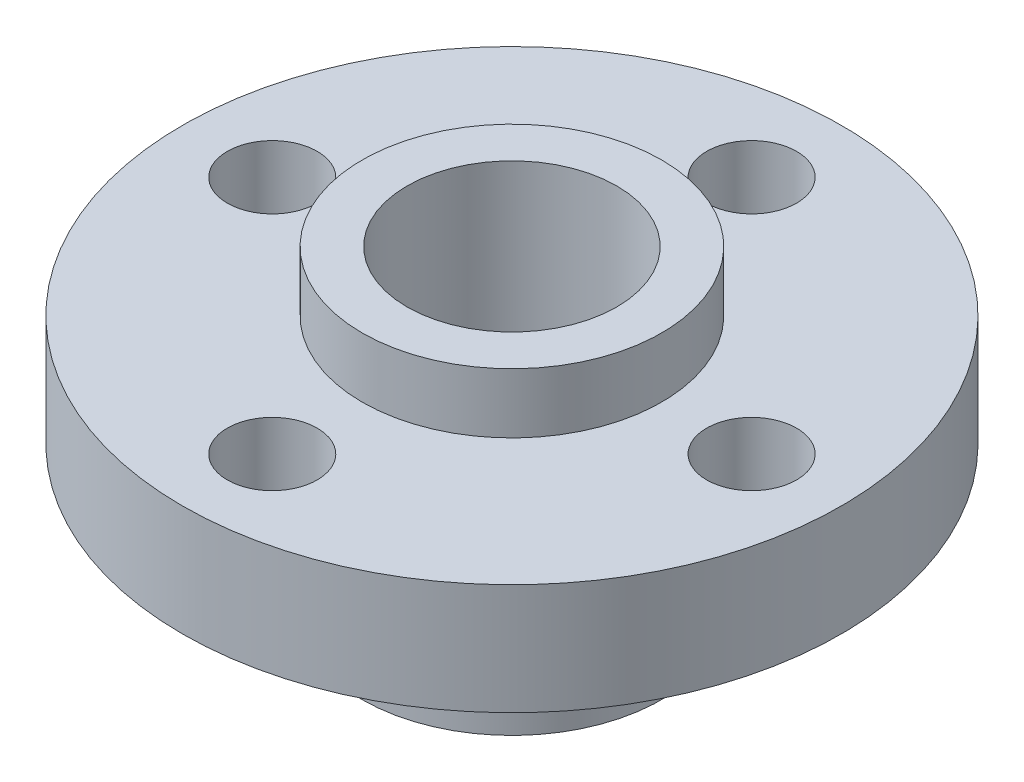
SolidWorks part; units mm, degrees
ref_plane "Front Plane" through (0, 0, 0) normal (0, 0, 1) x (1, 0, 0)
ref_plane "Top Plane" through (0, 0, 0) normal (0, 1, 0) x (1, 0, 0)
ref_plane "Right Plane" through (0, 0, 0) normal (1, 0, 0) x (0, 0, -1)
sketch "Sketch1" plane through (0, 0, 0) normal (0, 1, 0) x (1, 0, 0)
  circle A0 centre (0, 0) radius 11
  dimension "D1" = 22
extrude "Boss-Extrude1" add sketch "Sketch1" along normal blind 3.7
sketch "Sketch2" plane through (0, 3.7, 0) normal (0, 1, 0) x (1, 0, 0)
  circle A0 centre (0, 0) radius 8 construction
  circle A1 centre (0, 8) radius 1.5
  circle A2 centre (8, 0) radius 1.5
  circle A3 centre (0, -8) radius 1.5
  circle A4 centre (-8, 0) radius 1.5
  dimension "D1" = 16
  dimension "D2" = 3
extrude "Cut-Extrude1" cut sketch "Sketch2" against normal up to next
sketch "Sketch3" plane through (0, 3.7, 0) normal (0, 1, 0) x (1, 0, 0)
  circle A0 centre (0, 0) radius 5
  dimension "D1" = 10
extrude "Boss-Extrude2" add sketch "Sketch3" against normal blind 10.6 from offset 2
sketch "Sketch4" plane through (0, 5.7, 0) normal (0, 1, 0) x (1, 0, 0)
  circle A0 centre (0, 0) radius 3.5
  dimension "D1" = 7
extrude "Cut-Extrude2" cut sketch "Sketch4" against normal up to next
